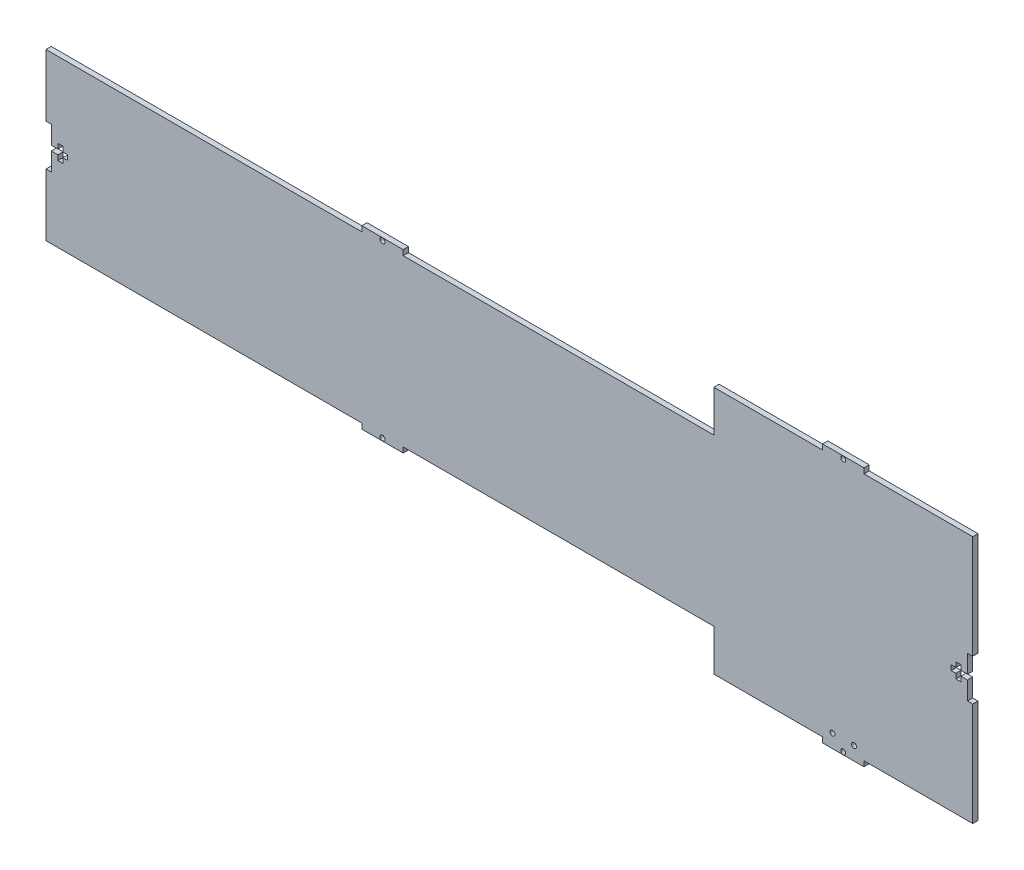
SolidWorks part; units mm, degrees
ref_plane "Front Plane" through (0, 0, 0) normal (0, 0, 1) x (1, 0, 0)
ref_plane "Top Plane" through (0, 0, 0) normal (0, 1, 0) x (1, 0, 0)
ref_plane "Right Plane" through (0, 0, 0) normal (1, 0, 0) x (0, 0, -1)
sketch "Sketch1" plane through (0, 0, 0) normal (0, 0, 1) x (1, 0, 0)
  line L5 (-200, -50) -> (200, 50) construction
  line L6 (-200, 12.5) -> (-200, 50) construction
  line L11 (-203.18, 50) -> (-203.18, 12.5)
  line L12 (303.18, 0) -> (-303.18, 0) construction
  line L13 (-203.18, 50) -> (-12.5, 50)
  line L14 (-203.18, -50) -> (-12.5, -50)
  line L25 (-200, -1.5) -> (-200, -12.5)
  line L26 (-200, 12.5) -> (-203.18, 12.5)
  line L44 (-200, 12.5) -> (-200, 1.5)
  line L45 (-200, -12.5) -> (-203.18, -12.5)
  line L47 (-200, 12.5) -> (-203.18, -12.5) construction
  line L48 (-200, -12.5) -> (-203.18, 12.5) construction
  line L66 (-190.18, 1.5) -> (-193, 1.5)
  line L67 (-190.18, 1.5) -> (-190.18, -1.5)
  line L68 (-190.18, -1.5) -> (-193, -1.5)
  line L70 (0, 50) -> (0, -50) construction
  line L76 (-196, 4.5) -> (-193, 4.5)
  line L77 (-196, 4.5) -> (-196, 1.5)
  line L78 (-196, -4.5) -> (-193, -4.5)
  line L79 (-193, 4.5) -> (-193, 1.5)
  line L80 (-196, 1.5) -> (-200, 1.5)
  line L81 (-193, -1.5) -> (-193, -4.5)
  line L82 (-196, -1.5) -> (-196, -4.5)
  line L87 (-196, -1.5) -> (-200, -1.5)
  line L99 (-203.18, -12.5) -> (-203.18, -50)
  line L101 (0, -50) -> (0, -53.18) construction
  line L102 (-12.5, -53.18) -> (12.5, -53.18)
  line L103 (-12.5, -53.18) -> (-12.5, -50)
  line L105 (12.5, -53.18) -> (12.5, -50)
  line L106 (-12.5, -53.18) -> (12.5, -50) construction
  line L107 (-12.5, -50) -> (12.5, -53.18) construction
  line L108 (12.5, -50) -> (200, -50)
  line L109 (12.5, 53.18) -> (12.5, 50)
  line L110 (-12.5, 53.18) -> (12.5, 53.18)
  line L111 (-12.5, 53.18) -> (-12.5, 50)
  line L112 (12.5, 50) -> (200, 50)
  line L113 (506.36, 0) -> (303.18, 0) construction
  line L118 (356.36, 75) -> (290.68, 75)
  line L119 (356.36, 75) -> (356.36, 12.5)
  line L120 (356.36, -75) -> (290.68, -75)
  line L121 (200, 75) -> (200, 50)
  line L122 (356.36, 75) -> (200, -75) construction
  line L123 (356.36, -75) -> (200, 75) construction
  line L124 (200, -50) -> (200, -75)
  line L125 (278.18, 100) -> (278.18, -100) construction
  line L126 (265.68, -78.18) -> (290.68, -78.18)
  line L127 (265.68, -78.18) -> (265.68, -75)
  line L129 (290.68, -78.18) -> (290.68, -75)
  line L130 (265.68, -78.18) -> (290.68, -75) construction
  line L131 (265.68, -75) -> (290.68, -78.18) construction
  line L132 (278.18, -78.18) -> (278.18, -100) construction
  line L133 (265.68, -75) -> (200, -75)
  line L134 (290.68, 78.18) -> (290.68, 75)
  line L135 (265.68, 78.18) -> (290.68, 78.18)
  line L136 (265.68, 78.18) -> (265.68, 75)
  line L137 (265.68, 75) -> (200, 75)
  line L138 (349.18, -1.5) -> (353.18, -1.5)
  line L139 (353.18, 12.5) -> (356.36, 12.5)
  line L140 (353.18, 12.5) -> (353.18, 1.5)
  line L141 (353.18, -12.5) -> (356.36, -12.5)
  line L143 (353.18, 12.5) -> (356.36, -12.5) construction
  line L144 (353.18, -12.5) -> (356.36, 12.5) construction
  line L145 (343.36, 1.5) -> (346.18, 1.5)
  line L146 (343.36, 1.5) -> (343.36, -1.5)
  line L147 (343.36, -1.5) -> (346.18, -1.5)
  line L149 (349.18, -1.5) -> (349.18, -4.5)
  line L150 (349.18, 1.5) -> (353.18, 1.5)
  line L151 (346.18, 4.5) -> (349.18, 4.5)
  line L152 (346.18, 4.5) -> (346.18, 1.5)
  line L153 (346.18, -4.5) -> (349.18, -4.5)
  line L154 (349.18, 4.5) -> (349.18, 1.5)
  line L155 (353.18, -1.5) -> (353.18, -12.5)
  line L156 (356.36, -12.5) -> (356.36, -75)
  line L157 (-200, -12.5) -> (-200, -50) construction
  line L158 (-200, 50) -> (200, -50) construction
  line L163 (346.18, -1.5) -> (346.18, -4.5)
  circle A2 centre (0, -51.59) radius 1.5
  circle A3 centre (0, 51.59) radius 1.5
  circle A5 centre (278.18, -76.59) radius 1.5
  circle A6 centre (278.18, 76.59) radius 1.5
  point P0 (0, 0)
  point P8 (-201.59, 0)
  point P13 (-295.09, 0)
  point P18 (-292.635, -0.75)
  point P19 (-294.5, 0)
  point P27 (304.77, 0)
  point P28 (278.18, 0)
  point P38 (278.18, -76.59)
  point P46 (0, -51.59)
  point P68 (354.77, 0)
  point P73 (498.27, 0)
  point P78 (497.68, 0)
  point P88 (0, 0)
  dimension "D5" = 13
  dimension "D12" = 3
  dimension "D14" = 150
  dimension "D17" = 3
  dimension "D2" = 100
  dimension "D3" = 25
  dimension "D4" = 3
  dimension "D6" = 4
  dimension "D7" = 3
  dimension "D8" = 3.18
  dimension "D9" = 9
  dimension "D10" = 25
  dimension "D11" = 3.18
  dimension "D13" = 156.36
  dimension "D15" = 25
  dimension "D16" = 3.18
  dimension "D18" = 25
  dimension "D19" = 3.18
  dimension "D20" = 13
  dimension "D21" = 3
  dimension "D22" = 3
  dimension "D23" = 4
  dimension "D24" = 9
  dimension "D25" = 400
extrude "Boss-Extrude1" add sketch "Sketch1" along normal blind 3.18
sketch "Sketch2" plane through (0, 0, 3.18) normal (0, 0, 1) x (1, 0, 0)
  line L0 (290.68, -75) -> (356.36, -75) construction
  line L1 (278.18, -78.18) -> (278.18, -56.6724) construction
  line L2 (265.68, -78.18) -> (290.68, -78.18) construction
  line L3 (284.68, -70) -> (278.18, -70) construction
  line L4 (278.18, -70) -> (271.68, -70) construction
  circle A0 centre (284.68, -70) radius 1.5
  circle A1 centre (271.68, -70) radius 1.5
  dimension "D1" = 13
  dimension "D3" = 3
  dimension "D4" = 3
  dimension "D2" = 5
extrude "Cut-Extrude1" cut sketch "Sketch2" against normal blind 10
